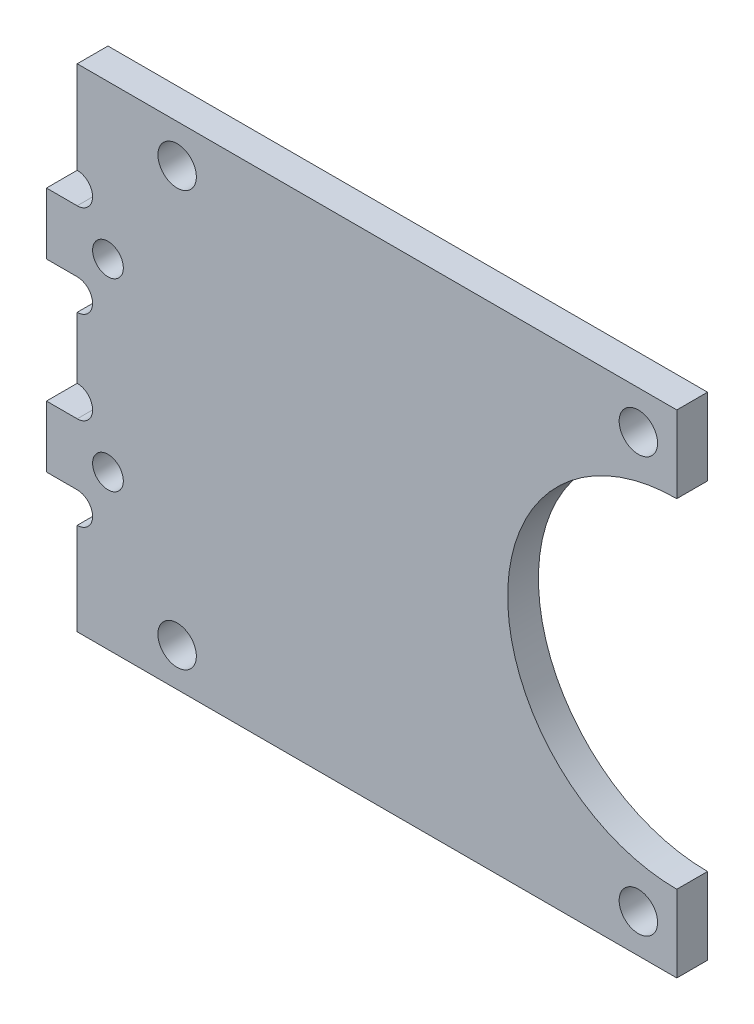
SolidWorks part; units mm, degrees
material "自訂玻璃纖維"
ref_plane "前基準面" through (0, 0, 0) normal (0, 0, 1) x (1, 0, 0)
ref_plane "上基準面" through (0, 0, 0) normal (0, 1, 0) x (1, 0, 0)
ref_plane "右基準面" through (0, 0, 0) normal (1, 0, 0) x (0, 0, -1)
sketch "草圖1" plane through (0, 0, 0) normal (0, 0, 1) x (1, 0, 0)
  line L0 (-17.2162, 10.1625) -> (13.2838, 10.1625)
  line L1 (13.2838, 10.1625) -> (13.2838, -21.8375)
  line L2 (13.2838, -21.8375) -> (-17.2162, -21.8375)
  line L3 (-25.7162, 2.1625) -> (-27.7162, 2.1625)
  line L4 (-27.7162, 2.1625) -> (-27.7162, -1.8375)
  line L5 (-17.2162, 10.1625) -> (-21.7162, 10.1625)
  line L6 (-27.7162, -1.8375) -> (-25.7162, -1.8375)
  line L7 (-17.2162, -21.8375) -> (-19.7162, -21.8375)
  line L8 (-25.7162, -3.8375) -> (-25.7162, -7.8375)
  line L9 (-21.7162, 10.1625) -> (-25.7162, 10.1625)
  line L10 (-25.7162, -15.8375) -> (-25.7162, -21.8375)
  line L11 (-19.7162, -21.8375) -> (-25.7162, -21.8375)
  line L12 (-25.7162, 10.1625) -> (-25.7162, 4.1625)
  line L13 (-27.7162, -9.8375) -> (-25.7162, -9.8375)
  line L14 (-27.7162, -13.8375) -> (-27.7162, -9.8375)
  line L15 (-25.7162, -13.8375) -> (-27.7162, -13.8375)
  circle A0 centre (-19.2162, 7.6625) radius 1.25
  circle A1 centre (-19.2162, -19.3375) radius 1.25
  circle A2 centre (10.7838, -19.3375) radius 1.25
  circle A3 centre (10.7838, 7.6625) radius 1.25
  arc A4 (-25.7162, 2.1625) -> (-25.7162, 4.1625) centre (-25.7162, 3.1625) ccw
  circle A5 centre (-23.7162, 0.1625) radius 1
  circle A6 centre (-23.7162, -11.8375) radius 1
  arc A7 (-25.7162, -1.8375) -> (-25.7162, -3.8375) centre (-25.7162, -2.8375) cw
  arc A8 (-25.7162, -9.8375) -> (-25.7162, -7.8375) centre (-25.7162, -8.8375) ccw
  arc A9 (-25.7162, -13.8375) -> (-25.7162, -15.8375) centre (-25.7162, -14.8375) cw
  dimension "D7" = 4
  dimension "D8" = 2
  dimension "D9" = 30
  dimension "D4" = 2.5
  dimension "D5" = 30
  dimension "D6" = 2
  dimension "D2" = 2.5
  dimension "D3" = 35
  dimension "D11" = 4
extrude "填料-伸長1" add sketch "草圖1" along normal blind 2
sketch "草圖4" plane through (0, 0, 0) normal (0, 0, -1) x (-1, 0, 0)
  line L0 (-13.2838, 5.1625) -> (-13.2838, -16.8375)
  line L1 (-13.2838, -21.8375) -> (-13.2838, 10.1625) construction
  arc A2 (-13.2838, 5.1625) -> (-13.2838, -16.8375) centre (-13.2838, -5.8375) cw
extrude "除料-伸長1" cut sketch "草圖4" against normal blind 2
